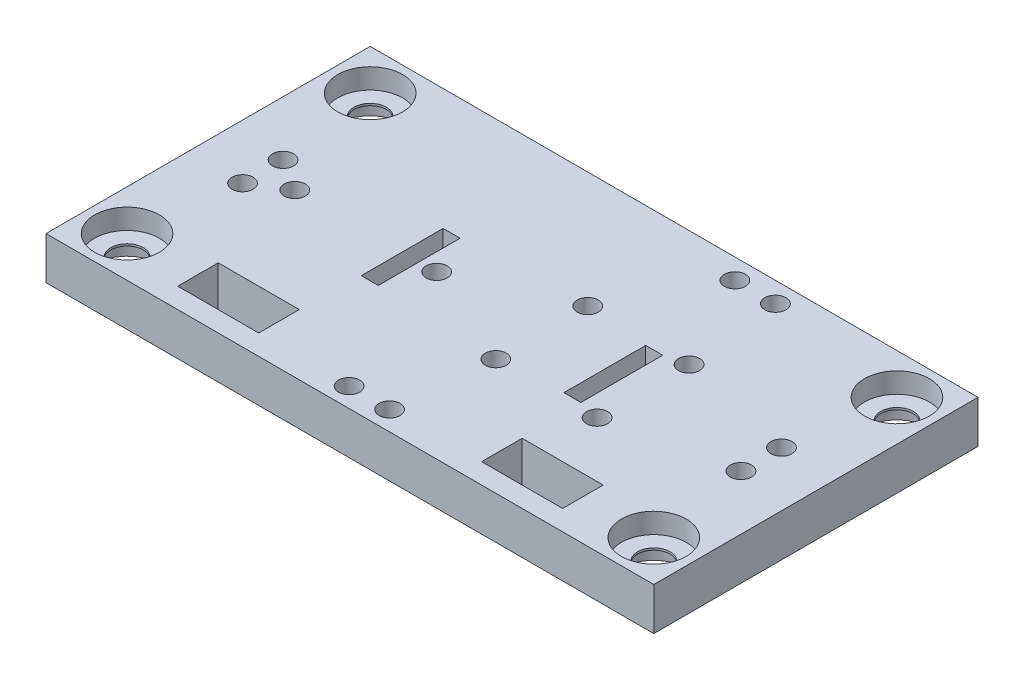
SolidWorks part; units mm, degrees
ref_plane "Front Plane" through (0, 0, 0) normal (0, 0, 1) x (1, 0, 0)
ref_plane "Top Plane" through (0, 0, 0) normal (0, 1, 0) x (1, 0, 0)
ref_plane "Right Plane" through (0, 0, 0) normal (1, 0, 0) x (0, 0, -1)
sketch "Sketch1" plane through (0, 0, 0) normal (0, 1, 0) x (1, 0, 0)
  line L1 (0, 0) -> (150, 0)
  line L2 (0, 0) -> (0, 80)
  line L3 (0, 80) -> (150, 80)
  line L4 (150, 0) -> (150, 80)
  dimension "D1" = 80
  dimension "D2" = 150
extrude "Boss-Extrude1" add sketch "Sketch1" along normal blind 10.5
sketch "Sketch10" plane through (0, 10.5, 0) normal (0, 1, 0) x (1, 0, 0)
  line L0 (75, 80) -> (75, 0) construction
  line L1 (0, 40) -> (150, 40) construction
  line L4 (0, 80) -> (0, 0)
  line L5 (0, 80) -> (0, 0) construction
  line L6 (0, 0) -> (150, 0)
  line L7 (0, 0) -> (150, 0) construction
  line L8 (150, 0) -> (150, 80)
  line L9 (150, 0) -> (150, 80) construction
  line L10 (150, 80) -> (0, 80)
  line L11 (150, 80) -> (0, 80) construction
  circle A0 centre (10, 10) radius 8
  circle A1 centre (140, 10) radius 8
  circle A3 centre (10, 70) radius 8
  circle A4 centre (140, 70) radius 8
  circle A5 centre (10, 10) radius 9
  circle A6 centre (10, 70) radius 9
  circle A7 centre (140, 70) radius 9
  circle A8 centre (140, 10) radius 9
  dimension "D4" = 16
  dimension "D2" = 10
  dimension "D3" = 10
  dimension "D1" = 0
  dimension "D5" = 1
extrude "Cut-Extrude8" cut sketch "Sketch10" against normal blind 5 contours A0 | A3 | A4 | A1 | L5 L7 L9 L11
ref_plane "MirrorPlane1" through (0, 5.25, 0) normal (0, 1, 0) x (1, 0, 0)
ref_plane "MirrorPlane2" through (0, 0, -40) normal (0, 0, 1) x (1, 0, 0)
ref_plane "MirrorPlane3" through (75, 0, 0) normal (-1, 0, 0) x (0, 0, 1)
mirror "Mirror1" about plane through (0, 5.25, 0) normal (0, 1, 0) of "Cut-Extrude8"
sketch "Sketch3" plane through (0, 10.5, 0) normal (0, 1, 0) x (1, 0, 0)
  line L0 (75, 80) -> (75, 0) construction
  line L5 (150, 80) -> (0, 80) construction
  line L6 (75, 5.775) -> (75, -5.775) construction
  line L7 (0, 0) -> (150, 0) construction
  line L8 (27.5, 15) -> (47.5, 15)
  line L9 (27.5, 15) -> (27.5, 5)
  line L10 (27.5, 5) -> (47.5, 5)
  line L11 (47.5, 15) -> (47.5, 5)
  line L12 (27.5, 15) -> (47.5, 5) construction
  line L13 (27.5, 5) -> (47.5, 15) construction
  line L15 (75, 80) -> (0, 0) construction
  line L16 (122.5, 5) -> (102.5, 5)
  line L17 (102.5, 15) -> (102.5, 5)
  line L18 (122.5, 15) -> (102.5, 15)
  line L19 (122.5, 15) -> (122.5, 5)
  point P0 (37.5, 10)
  point P16 (37.5, 40)
  dimension "D1" = 10
  dimension "D2" = 10
  dimension "D3" = 20
extrude "WireHoles" cut sketch "Sketch3" against normal up to next
sketch "Sketch6" plane through (0, 10.5, 0) normal (0, 1, 0) x (1, 0, 0)
  line L0 (75, 80) -> (75, 0) construction
  line L1 (150, 80) -> (0, 80) construction
  line L2 (0, 0) -> (150, 0) construction
  line L3 (38.9, 40) -> (21.4, 40) construction
  line L4 (73, 28.4) -> (4.8, 28.4) construction
  line L5 (73, 28.4) -> (73, 51.6) construction
  line L6 (73, 51.6) -> (4.8, 51.6) construction
  line L7 (4.8, 28.4) -> (4.8, 51.6) construction
  line L8 (73, 28.4) -> (4.8, 51.6) construction
  line L9 (73, 51.6) -> (4.8, 28.4) construction
  line L10 (38.9, 51.6) -> (38.9, 28.4) construction
  circle A0 centre (21.4, 40) radius 2.6
  circle A1 centre (56.4, 40) radius 2.6
  point P8 (38.9, 40)
  point P18 (75, 40)
  dimension "D5" = 5.2
  dimension "D1" = 68.2
  dimension "D2" = 23.2
  dimension "D3" = 2
  dimension "D4" = 17.5
extrude "4AACut" cut sketch "Sketch6" against normal blind 5.2
sketch "Sketch7" plane through (0, 10.5, 0) normal (0, 1, 0) x (1, 0, 0)
  line L0 (94.85, 51.35) -> (82.35, 51.35) construction
  line L1 (77, 42) -> (112.7, 42) construction
  line L2 (77, 42) -> (77, 60.7) construction
  line L3 (77, 60.7) -> (112.7, 60.7) construction
  line L4 (112.7, 42) -> (112.7, 60.7) construction
  line L5 (77, 42) -> (112.7, 60.7) construction
  line L6 (77, 60.7) -> (112.7, 42) construction
  line L7 (94.85, 60.7) -> (94.85, 42) construction
  line L8 (75, 80) -> (75, 0) construction
  line L9 (150, 80) -> (0, 80) construction
  line L10 (0, 0) -> (150, 0) construction
  line L11 (0, 40) -> (150, 40) construction
  line L12 (0, 80) -> (0, 0) construction
  line L13 (150, 0) -> (150, 80) construction
  circle A0 centre (82.35, 51.35) radius 2.6
  circle A1 centre (56.4, 40) radius 2.6 construction
  circle A2 centre (107.35, 51.35) radius 2.6
  circle A3 centre (82.35, 28.65) radius 2.6
  circle A4 centre (107.35, 28.65) radius 2.6
  point P0 (94.85, 51.35)
  dimension "D1" = 35.7
  dimension "D2" = 18.7
  dimension "D3" = 2
  dimension "D4" = 2
  dimension "D5" = 12.5
extrude "2AACut" cut sketch "Sketch7" against normal blind 5.2
sketch "Sketch5" plane through (0, 10.5, 0) normal (0, 1, 0) x (1, 0, 0)
  line L0 (75, 80) -> (75, 0) construction
  line L5 (150, 80) -> (0, 80) construction
  line L6 (0, 0) -> (150, 0) construction
  line L7 (50, 40) -> (75, 40) construction
  line L12 (47.9, 29.9) -> (52.1, 29.9)
  line L13 (47.9, 29.9) -> (47.9, 50.1)
  line L14 (47.9, 50.1) -> (52.1, 50.1)
  line L15 (52.1, 29.9) -> (52.1, 50.1)
  line L16 (47.9, 29.9) -> (52.1, 50.1) construction
  line L17 (47.9, 50.1) -> (52.1, 29.9) construction
  line L18 (102.1, 50.1) -> (97.9, 50.1)
  line L19 (97.9, 29.9) -> (97.9, 50.1)
  line L20 (102.1, 29.9) -> (97.9, 29.9)
  line L21 (102.1, 29.9) -> (102.1, 50.1)
  point P0 (50, 40)
  dimension "D1" = 25
  dimension "D2" = 4.2
  dimension "D3" = 20.2
extrude "ArduinoMegaCut" cut sketch "Sketch5" against normal blind 5.2
sketch "Sketch8" plane through (0, 10.5, 0) normal (0, 1, 0) x (1, 0, 0)
  line L0 (150, 80) -> (0, 80) construction
  line L5 (62.4, -2.5) -> (87.6, -2.5) construction
  line L6 (62.4, -2.5) -> (62.4, 12.1) construction
  line L7 (62.4, 12.1) -> (87.6, 12.1) construction
  line L8 (87.6, -2.5) -> (87.6, 12.1) construction
  line L9 (75, 80) -> (75, 0) construction
  line L10 (0, 0) -> (150, 0) construction
  line L11 (87.6, 4.8) -> (62.4, 4.8) construction
  circle A1 centre (70, 4.8) radius 2.6
  circle A2 centre (56.4, 40) radius 2.6 construction
  circle A3 centre (80, 4.8) radius 2.6
  point P10 (75, 12.1)
  dimension "D1" = 14.6
  dimension "D2" = 25.2
  dimension "D3" = 2.5
  dimension "D4" = 5
extrude "MPUCut" cut sketch "Sketch8" against normal blind 5.2
sketch "Sketch9" plane through (0, 10.5, 0) normal (0, 1, 0) x (1, 0, 0)
  line L0 (150, 0) -> (150, 80) construction
  line L1 (125, 51.225) -> (148, 51.225)
  line L2 (125, 51.225) -> (125, 28.775)
  line L3 (125, 28.775) -> (148, 28.775)
  line L4 (148, 51.225) -> (148, 28.775)
  line L5 (125, 51.225) -> (148, 28.775) construction
  line L6 (125, 28.775) -> (148, 51.225) construction
  line L9 (0, 40) -> (150, 40) construction
  line L10 (0, 80) -> (0, 0) construction
  line L11 (75, 80) -> (75, 0) construction
  line L12 (150, 80) -> (0, 80) construction
  line L13 (0, 0) -> (150, 0) construction
  circle A0 centre (136.5, 45) radius 2.6
  circle A1 centre (107.35, 51.35) radius 2.6 construction
  circle A2 centre (136.5, 35) radius 2.6
  circle A3 centre (13.5, 35) radius 2.6
  circle A4 centre (13.5, 45) radius 2.6
  point P0 (136.5, 40)
  dimension "D1" = 22.45
  dimension "D2" = 23
  dimension "D3" = 5
  dimension "D4" = 2
extrude "Cut-Extrude7" cut sketch "Sketch9" against normal up to next contours A0 | A2 | A4 | A3
sketch "Sketch11" plane through (0, 5.5, 0) normal (0, 1, 0) x (1, 0, 0)
  line L0 (0, 40) -> (150, 40) construction
  line L1 (0, 80) -> (0, 0) construction
  line L2 (150, 0) -> (150, 80) construction
  line L3 (75, 80) -> (75, 0) construction
  line L4 (150, 80) -> (0, 80) construction
  line L5 (0, 0) -> (150, 0) construction
  circle A0 centre (10, 10) radius 4
  circle A1 centre (10, 70) radius 4
  circle A2 centre (140, 70) radius 4
  circle A3 centre (140, 10) radius 4
  dimension "D1" = 8
extrude "Cut-Extrude9" cut sketch "Sketch11" against normal up to surface (0.5 mm away) up to face at (10, 5, -62)
sketch "Sketch12" plane through (0, 10.5, 0) normal (0, 1, 0) x (1, 0, 0)
  line L0 (100, 80) -> (100, 0) construction
  line L1 (150, 80) -> (0, 80) construction
  line L2 (0, 0) -> (150, 0) construction
  line L3 (150, 0) -> (150, 80) construction
  circle A0 centre (95, 75) radius 2.6
  circle A1 centre (82.35, 51.35) radius 2.6 construction
  circle A4 centre (105, 75) radius 2.6
  dimension "D1" = 50
  dimension "D2" = 10
  dimension "D3" = 5
extrude "Cut-Extrude10" cut sketch "Sketch12" against normal blind 5
equation "\"Depth\"= 5.20"
